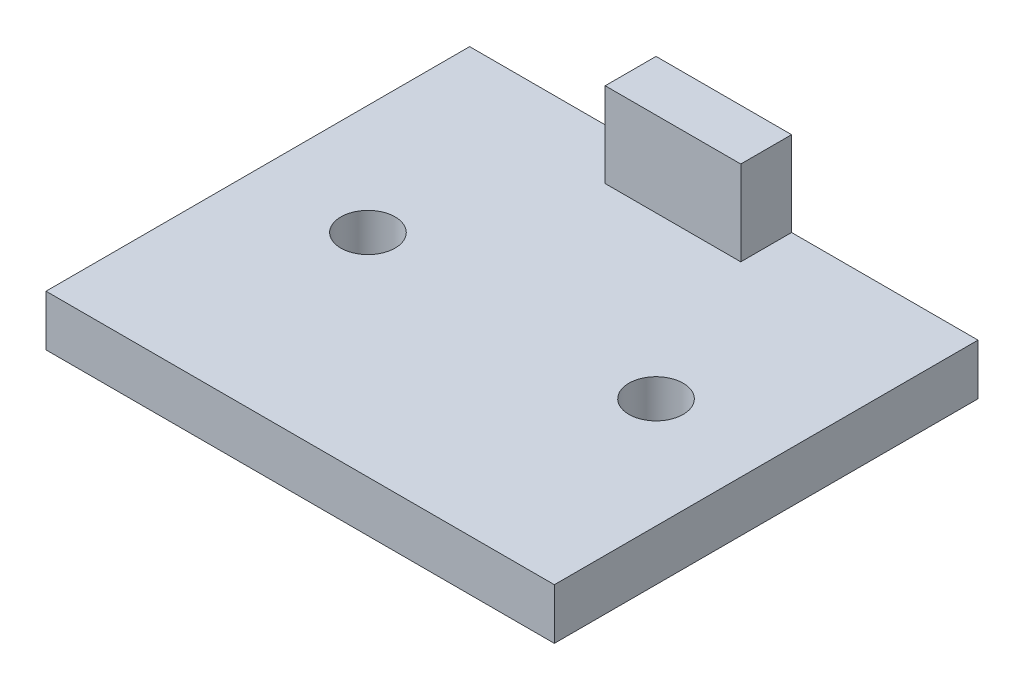
SolidWorks part; units mm, degrees
ref_plane "Front Plane" through (0, 0, 0) normal (0, 0, 1) x (1, 0, 0)
ref_plane "Top Plane" through (0, 0, 0) normal (0, 1, 0) x (1, 0, 0)
ref_plane "Right Plane" through (0, 0, 0) normal (1, 0, 0) x (0, 0, -1)
sketch "Sketch1" plane through (0, 0, 0) normal (0, 1, 0) x (1, 0, 0)
  line L1 (-22.2906, 14.6552) -> (7.7094, 14.6552)
  line L2 (-22.2906, 14.6552) -> (-22.2906, -10.3448)
  line L3 (-22.2906, -10.3448) -> (7.7094, -10.3448)
  line L4 (7.7094, 14.6552) -> (7.7094, -10.3448)
  dimension "D1" = 25
  dimension "D2" = 30
extrude "Boss-Extrude1" add sketch "Sketch1" along normal blind 3 contours L1 L4 L3 L2
sketch "Sketch2" plane through (0, 3, 0) normal (0, 1, 0) x (1, 0, 0)
  circle A0 centre (-15.7906, 2.1552) radius 1.6
  circle A1 centre (1.2094, 2.1552) radius 1.6
extrude "Cut-Extrude2" cut sketch "Sketch2" against normal blind 10
sketch "Sketch3" plane through (0, 3, 0) normal (0, 1, 0) x (1, 0, 0)
  line L0 (-11.2906, 11.6552) -> (-11.2906, 14.6552)
  line L1 (-11.2906, 11.6552) -> (-3.2906, 11.6552)
  line L2 (-11.2906, 14.6552) -> (-3.2906, 14.6552)
  line L3 (-3.2906, 11.6552) -> (-3.2906, 14.6552)
  dimension "D1" = 8
  dimension "D2" = 3
extrude "Boss-Extrude2" add sketch "Sketch3" along normal blind 5
